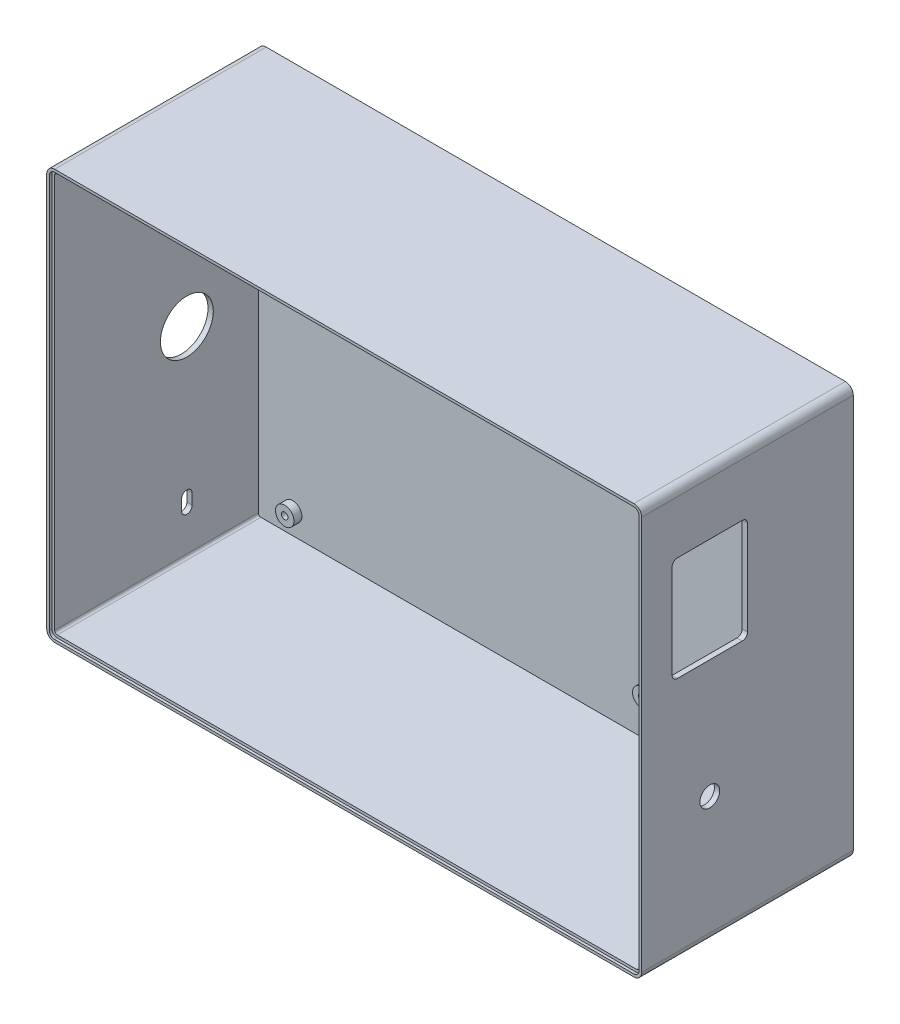
SolidWorks part; units mm, degrees
ref_plane "前视基准面" through (0, 0, 0) normal (0, 0, 1) x (1, 0, 0)
ref_plane "上视基准面" through (0, 0, 0) normal (0, 1, 0) x (1, 0, 0)
ref_plane "右视基准面" through (0, 0, 0) normal (1, 0, 0) x (0, 0, -1)
other "Configuration Table"
sketch "草图1" plane through (0, 0, 0) normal (0, 0, 1) x (1, 0, 0)
  line L1 (0, 0) -> (225, 0)
  line L2 (0, 0) -> (0, -155)
  line L3 (0, -155) -> (225, -155)
  line L4 (225, 0) -> (225, -155)
  dimension "D1" = 155
  dimension "D2" = 225
extrude "凸台-拉伸1" add sketch "草图1" along normal blind 80
fillet "圆角1" radius 3 4 edges at (0, -155, 40) (225, -155, 40) (225, 0, 40) (0, 0, 40)
shell "抽壳1" thickness 2
sketch "草图2" plane through (0, 0, 2) normal (0, 0, 1) x (1, 0, 0)
  line L0 (223, -77.5) -> (2, -77.5) construction
  line L1 (223, -152) -> (223, -3) construction
  line L2 (2, -3) -> (2, -152) construction
  line L3 (223, -152) -> (223, -3) construction
  circle A0 centre (217, -20) radius 3.5
  circle A1 centre (152, -20) radius 3.5
  circle A2 centre (152, -135) radius 3.5
  circle A3 centre (217, -135) radius 3.5
  circle A4 centre (217, -20) radius 1.25
  circle A5 centre (152, -20) radius 1.25
  circle A6 centre (152, -135) radius 1.25
  circle A7 centre (217, -135) radius 1.25
  dimension "D2" = 7
  dimension "D6" = 2.5
  dimension "D1" = 57.5
  dimension "D3" = 6
  dimension "D4" = 2
  dimension "D5" = 2
  dimension "D7" = 2
  dimension "D8" = 2
extrude "凸台-拉伸2" add sketch "草图2" along normal blind 5
sketch "草图4" plane through (225, 0, 0) normal (1, 0, 0) x (0, 0, -1)
  line L0 (0, -152) -> (0, -3) construction
  line L1 (-68.5, -23) -> (-40, -23)
  line L2 (-68.5, -23) -> (-68.5, -62.5)
  line L3 (-68.5, -62.5) -> (-40, -62.5)
  line L4 (-40, -23) -> (-40, -62.5)
  line L5 (0, -3) -> (-80, -3) construction
  dimension "D1" = 28.5
  dimension "D2" = 39.5
  dimension "D3" = 40
  dimension "D4" = 20
extrude "切除-拉伸3" cut sketch "草图4" against normal blind 3
fillet "圆角2" radius 2 4 edges at (224, -62.5, 40) (224, -62.5, 68.5) (224, -23, 68.5) (224, -23, 40)
sketch "草图5" plane through (0, 0, 0) normal (-1, 0, 0) x (0, 0, 1)
  line L0 (0, -77.5) -> (80, -77.5) construction
  line L1 (0, -3) -> (0, -152) construction
  line L2 (80, -3) -> (80, -152) construction
  circle A0 centre (29, -77.5) radius 10
  dimension "D1" = 20
  dimension "D2" = 29
extrude "切除-拉伸4" cut sketch "草图5" against normal blind 3
sketch "草图6" plane through (225, 0, 0) normal (1, 0, 0) x (0, 0, -1)
  line L0 (-54.25, -62.5) -> (-54.25, -152) construction
  line L1 (-66.5, -62.5) -> (-42, -62.5) construction
  line L2 (-80, -152) -> (0, -152) construction
  circle A0 centre (-54.25, -107.25) radius 3.75
  dimension "D1" = 7.5
extrude "切除-拉伸5" cut sketch "草图6" against normal blind 3
sketch "草图7" plane through (0, 0, 0) normal (-1, 0, 0) x (0, 0, 1)
  line L0 (29, -77.5) -> (29, -152) construction
  line L1 (0, -152) -> (80, -152) construction
  line L2 (29, -133) -> (29, -137) construction
  line L3 (31, -133) -> (31, -137)
  line L4 (27, -133) -> (27, -137)
  arc A1 (31, -133) -> (27, -133) centre (29, -133) ccw
  arc A2 (27, -137) -> (31, -137) centre (29, -137) ccw
  point P7 (29, -135)
  dimension "D1" = 4
  dimension "D2" = 2
  dimension "D3" = 15
extrude "切除-拉伸6" cut sketch "草图7" against normal blind 3
sketch "草图8" plane through (0, 0, 80) normal (0, 0, 1) x (1, 0, 0)
  line L0 (3, -154) -> (222, -154)
  line L1 (224, -152) -> (224, -3)
  line L2 (222, -1) -> (3, -1)
  line L3 (1, -3) -> (1, -152)
  line L4 (3, -153) -> (222, -153)
  line L5 (223, -152) -> (223, -3)
  line L6 (222, -2) -> (3, -2)
  line L7 (2, -3) -> (2, -152)
  line L8 (3, -153) -> (222, -153)
  line L9 (223, -152) -> (223, -3)
  line L10 (222, -2) -> (3, -2)
  line L11 (2, -3) -> (2, -152)
  arc A0 (222, -154) -> (224, -152) centre (222, -152) ccw
  arc A1 (224, -3) -> (222, -1) centre (222, -3) ccw
  arc A2 (3, -1) -> (1, -3) centre (3, -3) ccw
  arc A3 (1, -152) -> (3, -154) centre (3, -152) ccw
  arc A4 (222, -153) -> (223, -152) centre (222, -152) ccw
  arc A5 (223, -3) -> (222, -2) centre (222, -3) ccw
  arc A6 (3, -2) -> (2, -3) centre (3, -3) ccw
  arc A7 (2, -152) -> (3, -153) centre (3, -152) ccw
  arc A8 (222, -153) -> (223, -152) centre (222, -152) ccw
  arc A9 (223, -3) -> (222, -2) centre (222, -3) ccw
  arc A10 (3, -2) -> (2, -3) centre (3, -3) ccw
  arc A11 (2, -152) -> (3, -153) centre (3, -152) ccw
  dimension "D1" = 0
  dimension "D2" = 1
extrude "切除-拉伸7" cut sketch "草图8" against normal blind 1
sketch "草图9" plane through (0, 0, 2) normal (0, 0, 1) x (1, 0, 0)
  line L0 (222, 0) -> (3, 0) construction
  line L1 (0, -3) -> (0, -152) construction
  circle A0 centre (15, -10) radius 3.5
  circle A1 centre (210, -10) radius 3.5
  circle A2 centre (210, -145) radius 3.5
  circle A3 centre (15, -145) radius 3.5
  dimension "D1" = 7
  dimension "D2" = 10
  dimension "D3" = 15
  dimension "D4" = 2
  dimension "D5" = 2
extrude "凸台-拉伸4" add sketch "草图9" along normal blind 3
sketch "草图10" plane through (0, 0, 5) normal (0, 0, 1) x (1, 0, 0)
  circle A0 centre (15, -10) radius 1.25
  circle A1 centre (210, -10) radius 1.25
  circle A2 centre (210, -145) radius 1.25
  circle A3 centre (15, -145) radius 1.25
  dimension "D1" = 2.5
  dimension "D2" = 2
  dimension "D3" = 2
extrude "切除-拉伸8" cut sketch "草图10" against normal blind 5
sketch "草图11" plane through (0, 0, 2) normal (0, 0, 1) x (1, 0, 0)
  circle A0 centre (217, -20) radius 1.25 construction
  circle A1 centre (217, -20) radius 1.25
  circle A2 centre (152, -20) radius 1.25 construction
  circle A3 centre (152, -20) radius 1.25
  circle A4 centre (217, -135) radius 1.25 construction
  circle A5 centre (217, -135) radius 1.25
  circle A6 centre (152, -135) radius 1.25 construction
  circle A7 centre (152, -135) radius 1.25
extrude "切除-拉伸9" cut sketch "草图11" against normal blind 2
